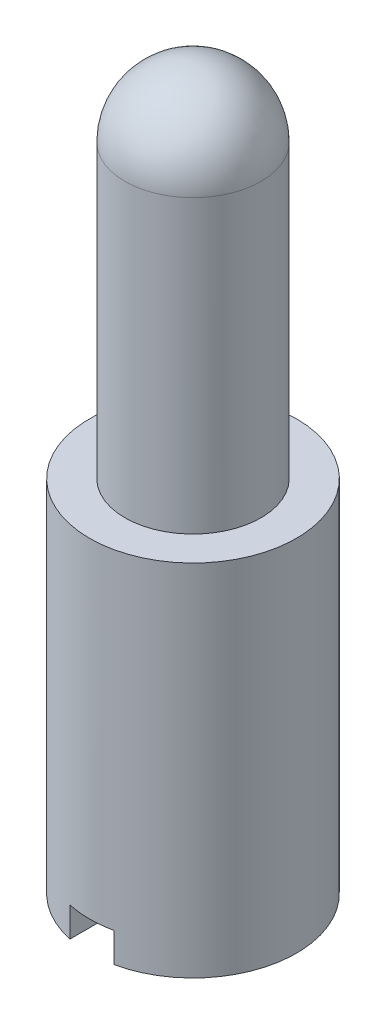
SolidWorks part; units mm, degrees
ref_plane "Front Plane" through (0, 0, 0) normal (0, 0, 1) x (1, 0, 0)
ref_plane "Top Plane" through (0, 0, 0) normal (0, 1, 0) x (1, 0, 0)
ref_plane "Right Plane" through (0, 0, 0) normal (1, 0, 0) x (0, 0, -1)
sketch "Sketch1" plane through (0, 0, 0) normal (0, 0, 1) x (1, 0, 0)
  line L0 (0, 19.05) -> (0, 0)
  line L1 (0, 0) -> (2.7432, 0)
  line L2 (2.7432, 0) -> (2.7432, 9.525)
  line L3 (2.7432, 9.525) -> (1.8034, 9.525)
  line L4 (1.8034, 9.525) -> (1.8034, 17.2466)
  arc A0 (1.8034, 17.2466) -> (0, 19.05) centre (0, 17.2466) ccw
  point P8 (0, 0)
  dimension "D1" = 19.05
  dimension "D2" = 9.525
  dimension "D3" = 2.7432
  dimension "D4" = 1.8034
revolve "Revolve1" add sketch "Sketch1" angle 360 about L0
cosmetic thread "Cosmetic Thread1" parameters "D2"=4.2266
sketch "Sketch2" plane through (0, 0, 0) normal (0, 0, 1) x (1, 0, 0)
  line L1 (-0.5842, 0) -> (0.5842, 0)
  line L2 (-0.5842, 0) -> (-0.5842, 0.7874)
  line L3 (-0.5842, 0.7874) -> (0.5842, 0.7874)
  line L4 (0.5842, 0) -> (0.5842, 0.7874)
  dimension "D1" = 0.7874
  dimension "D2" = 1.1684
extrude "Cut-Extrude1" cut sketch "Sketch2" against normal through all both and the other way through all
